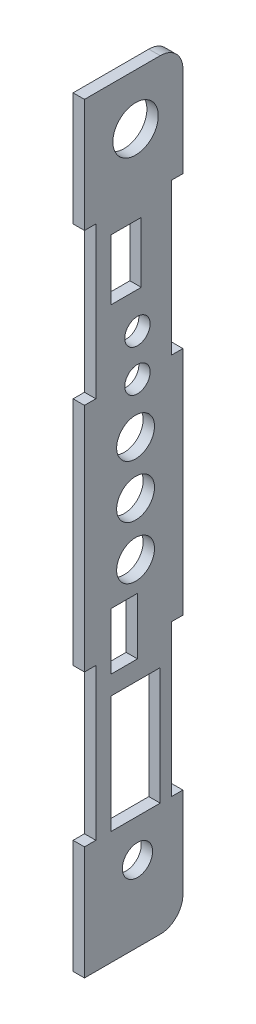
SolidWorks part; units mm, degrees
material "ABS"
ref_plane "前视基准面" through (0, 0, 0) normal (0, 0, 1) x (1, 0, 0)
ref_plane "上视基准面" through (0, 0, 0) normal (0, 1, 0) x (1, 0, 0)
ref_plane "右视基准面" through (0, 0, 0) normal (1, 0, 0) x (0, 0, -1)
sketch "草图1" plane through (0, 0, 0) normal (1, 0, 0) x (0, 0, -1)
  line L0 (-147.4722, 90.8634) -> (-147.4722, 54.8634) construction
  line L1 (-173.4722, 94.5306) -> (-147.4722, 94.5306)
  line L2 (-173.4722, 94.5306) -> (-173.4722, -106.4694)
  line L3 (-173.4722, -106.4694) -> (-147.4722, -106.4694)
  line L4 (-147.4722, 94.5306) -> (-147.4722, -106.4694)
  dimension "D1" = 201
  dimension "D2" = 26
extrude "凸台-拉伸1" add sketch "草图1" along normal blind 3
sketch "草图5" plane through (3, 0, 0) normal (1, 0, 0) x (0, 0, -1)
  line L0 (-147.4722, -106.4694) -> (-147.4722, 94.5306) construction
  line L1 (-147.4722, 64.5306) -> (-150.4722, 64.5306)
  line L2 (-147.4722, 64.5306) -> (-147.4722, 24.5306)
  line L3 (-147.4722, 24.5306) -> (-150.4722, 24.5306)
  line L4 (-150.4722, 64.5306) -> (-150.4722, 24.5306)
  line L5 (-147.4722, 94.5306) -> (-173.4722, 94.5306) construction
  line L6 (-147.4722, -5.9694) -> (-173.4722, -5.9694) construction
  line L7 (-173.4722, 94.5306) -> (-173.4722, -106.4694) construction
  line L8 (-160.4722, -106.4694) -> (-160.4722, 94.5306) construction
  line L9 (-173.4722, -106.4694) -> (-147.4722, -106.4694) construction
  line L10 (-170.4722, 64.5306) -> (-170.4722, 24.5306)
  line L11 (-173.4722, 24.5306) -> (-170.4722, 24.5306)
  line L12 (-173.4722, 64.5306) -> (-173.4722, 24.5306)
  line L13 (-173.4722, 64.5306) -> (-170.4722, 64.5306)
  line L14 (-173.4722, -76.4694) -> (-170.4722, -76.4694)
  line L15 (-173.4722, -76.4694) -> (-173.4722, -36.4694)
  line L16 (-173.4722, -36.4694) -> (-170.4722, -36.4694)
  line L17 (-170.4722, -76.4694) -> (-170.4722, -36.4694)
  line L18 (-150.4722, -76.4694) -> (-150.4722, -36.4694)
  line L19 (-147.4722, -36.4694) -> (-150.4722, -36.4694)
  line L20 (-147.4722, -76.4694) -> (-147.4722, -36.4694)
  line L21 (-147.4722, -76.4694) -> (-150.4722, -76.4694)
  dimension "D1" = 3
  dimension "D2" = 40
  dimension "D3" = 30
extrude "切除-拉伸1" cut sketch "草图5" against normal blind 3
fillet "圆角1" radius 6 1 edges at (1.5, 94.5306, 147.4722)
fillet "圆角2" radius 6 1 edges at (1.5, -106.4694, 147.4722)
sketch "草图6" plane through (0, 0, 0) normal (-1, 0, 0) x (0, 0, 1)
  line L0 (167.4722, -106.4694) -> (167.4722, 94.5306) construction
  line L1 (173.4722, -106.4694) -> (153.4722, -106.4694) construction
  line L2 (153.4722, 94.5306) -> (173.4722, 94.5306) construction
  line L3 (170.4722, -76.4694) -> (170.4722, -36.4694) construction
  line L5 (166.4722, -76.4694) -> (153.4722, -76.4694)
  line L6 (166.4722, -76.4694) -> (166.4722, -45.4694)
  line L7 (166.4722, -45.4694) -> (153.4722, -45.4694)
  line L8 (153.4722, -76.4694) -> (153.4722, -45.4694)
  line L9 (166.4722, -40.4694) -> (159.4722, -40.4694)
  line L10 (166.4722, -40.4694) -> (166.4722, -25.4694)
  line L11 (166.4722, -25.4694) -> (159.4722, -25.4694)
  line L12 (159.4722, -40.4694) -> (159.4722, -25.4694)
  line L13 (166.4722, 44.0306) -> (158.4722, 44.0306)
  line L14 (166.4722, 44.0306) -> (166.4722, 60.0306)
  line L15 (166.4722, 60.0306) -> (158.4722, 60.0306)
  line L16 (158.4722, 44.0306) -> (158.4722, 60.0306)
  circle A0 centre (159.4722, -86.4694) radius 4
  circle A1 centre (159.9722, -17.4694) radius 5
  circle A2 centre (159.9722, -3.4694) radius 5
  circle A3 centre (159.9722, 10.5306) radius 5
  circle A4 centre (159.4722, 23.5306) radius 3.3557
  circle A5 centre (159.4722, 34.5306) radius 3.3557
  circle A6 centre (159.9722, 81.0306) radius 6
  point P18 (159.4722, -32.9694)
  dimension "D2" = 8
  dimension "D13" = 10
  dimension "D16" = 71
  dimension "D23" = 12
  dimension "D1" = 3
  dimension "D3" = 20
  dimension "D4" = 8
  dimension "D5" = 1
  dimension "D6" = 30
  dimension "D7" = 14
  dimension "D8" = 31
  dimension "D9" = 66
  dimension "D10" = 8
  dimension "D11" = 1
  dimension "D12" = 15
  dimension "D14" = 89
  dimension "D15" = 7.5
  dimension "D17" = 8
  dimension "D18" = 150.5
  dimension "D19" = 16
  dimension "D20" = 9
  dimension "D21" = 1
  dimension "D22" = 13.5
  dimension "D24" = 7.5
  dimension "D25" = 117
extrude "切除-拉伸2" cut sketch "草图6" against normal blind 3
